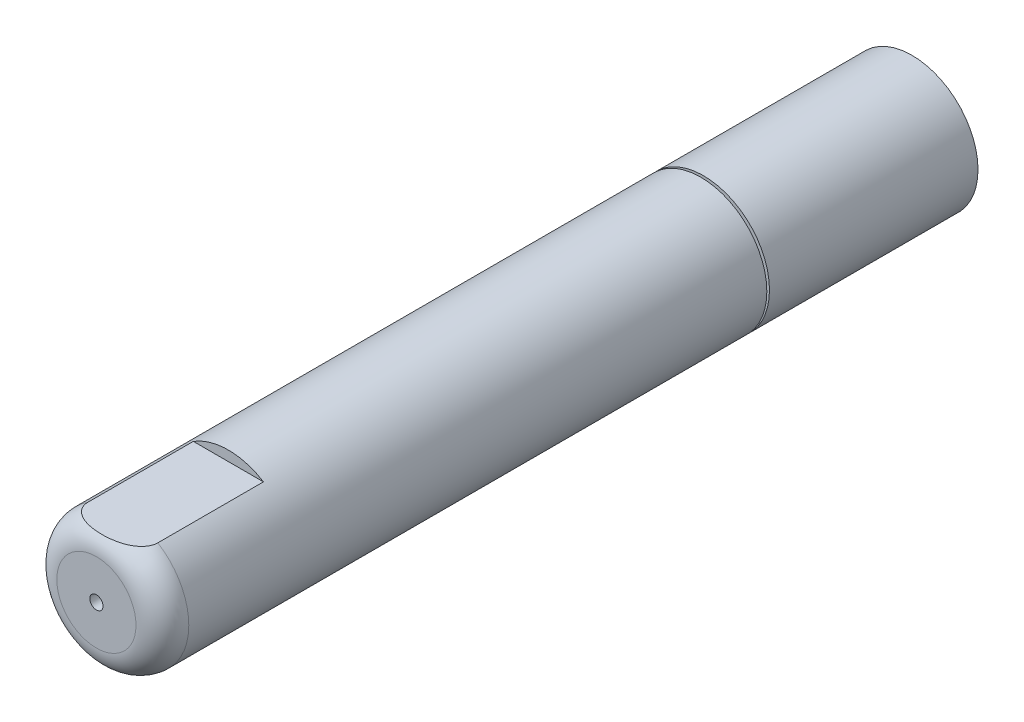
SolidWorks part; units mm, degrees
material "AISI 4340 Steel, annealed"
ref_plane "Front Plane" through (0, 0, 0) normal (0, 0, 1) x (1, 0, 0)
ref_plane "Top Plane" through (0, 0, 0) normal (0, 1, 0) x (1, 0, 0)
ref_plane "Right Plane" through (0, 0, 0) normal (1, 0, 0) x (0, 0, -1)
sketch "Sketch1" plane through (0, 0, 0) normal (1, 0, 0) x (0, 0, -1)
  line L0 (24.7402, 48.1333) -> (47.6402, 48.1333)
  line L2 (52.6402, 48.1333) -> (55.6402, 48.1333)
  line L3 (55.6402, 48.1333) -> (55.6402, 45.6333)
  line L5 (24.7402, 45.6333) -> (24.7402, 48.1333)
  line L6 (15.9402, 45.6333) -> (309.0068, 45.6333) construction
  line L8 (50.6402, 48.1333) -> (52.6402, 48.1333)
  line L9 (47.7402, 47.6333) -> (47.7402, 48.1333)
  line L10 (24.7402, 45.6333) -> (55.6402, 45.6333)
  line L11 (47.6402, 47.6333) -> (47.6402, 48.1333)
  line L12 (47.7402, 48.1333) -> (50.6402, 48.1333)
  line L13 (47.7402, 47.6333) -> (47.6402, 47.6333)
  line L15 (47.7402, 45.6333) -> (47.7402, 48.1333) construction
  dimension "D1" = 2.5
  dimension "D2" = 23
  dimension "D4" = 3
  dimension "D5" = 3
  dimension "D6" = 0.5
  dimension "D7" = 2.5
  dimension "D8" = 0.1
revolve "Revolve1" add sketch "Sketch1" angle 360 about L6
sketch "Sketch2" plane through (0, 0, -24.7402) normal (0, 0, 1) x (1, 0, 0)
  line L1 (2.4972, 45.5154) -> (2.4972, 47.7512)
  line L2 (-2.4972, 45.7512) -> (-2.4972, 47.7512)
  line L3 (-1.3283, 47.7512) -> (1.3283, 47.7512)
  arc A1 (2.4972, 45.5154) -> (2.4972, 45.7512) centre (0, 45.6333) ccw
  arc A2 (-2.4972, 45.7512) -> (2.4972, 45.7512) centre (0, 45.6333) ccw
  arc A3 (1.3283, 47.7512) -> (0, 48.1333) centre (0, 45.6333) ccw
  circle A4 centre (0, 45.6333) radius 2.5
  arc A5 (1.3283, 47.7512) -> (-1.3283, 47.7512) centre (0, 45.6333) ccw
  point P1 (0, 0)
  point P5 (2.4972, 45.6333)
  point P6 (2.4972, 73.906)
  point P7 (-2.4972, 45.6333)
  point P8 (-2.4972, 73.906)
  circle M4 centre (0, 45.6333) radius 2.5
  dimension "D3" = 5
  dimension "D1" = 2
sketch "Sketch3" plane through (0, 0, -24.7402) normal (0, 0, 1) x (1, 0, 0)
  circle A0 centre (0, 45.6333) radius 0.25
  dimension "D1" = 0.5
extrude "Cut-Extrude1" cut sketch "Sketch3" against normal blind 50
fillet "Fillet1" radius 1 1 edges at (2.5, 45.6333, -24.7402)
extrude "Cut-Extrude2" cut sketch "Sketch2" against normal blind 5 contours L3 M4
